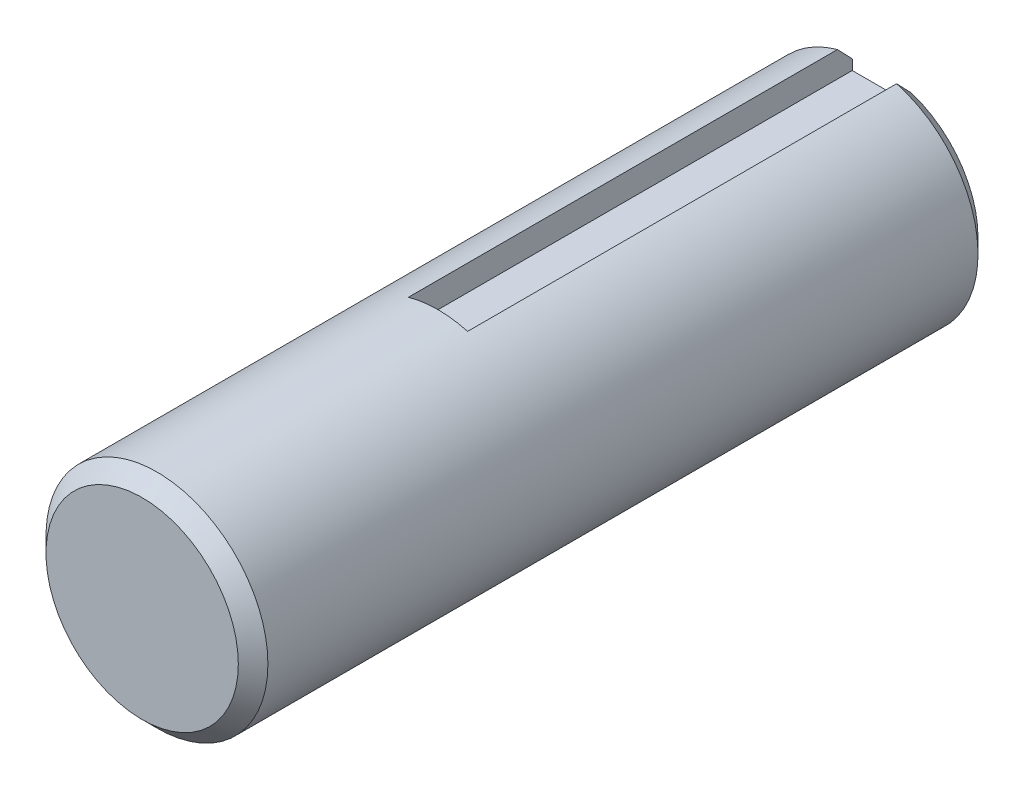
SolidWorks part; units mm, degrees
ref_plane "Front Plane" through (0, 0, 0) normal (0, 0, 1) x (1, 0, 0)
ref_plane "Top Plane" through (0, 0, 0) normal (0, 1, 0) x (1, 0, 0)
ref_plane "Right Plane" through (0, 0, 0) normal (1, 0, 0) x (0, 0, -1)
sketch "Sketch1" plane through (0, 0, 0) normal (0, 0, 1) x (1, 0, 0)
  circle A0 centre (0, 0) radius 15
  dimension "D1" = 30
extrude "Boss-Extrude1" add sketch "Sketch1" along normal blind 100
chamfer "Chamfer1" distance 2 angle 45 1 edges at (15, 0, 100)
chamfer "Chamfer2" distance 2 angle 45 1 edges at (15, 0, 0)
sketch "Sketch2" plane through (0, 0, 0) normal (0, 0, -1) x (-1, 0, 0)
  line L0 (0, 0) -> (0, 11)
  line L1 (-4, 11) -> (4, 11)
  line L2 (-4, 11) -> (-4, 14.4568)
  line L3 (4, 11) -> (4, 14.4568)
  line L4 (-4, 14.4568) -> (-4, 16.0034)
  line L5 (-4, 16.0034) -> (4, 16.0034)
  line L6 (4, 16.0034) -> (4, 14.4568)
  circle A0 centre (0, 0) radius 15 construction
  point P7 (0, 11)
  circle M8 centre (0, 0) radius 13
  dimension "D1" = 11
  dimension "D2" = 8
extrude "Cut-Extrude1" cut sketch "Sketch2" against normal blind 60 contours L6 L5 L4 L2 L3 M8
